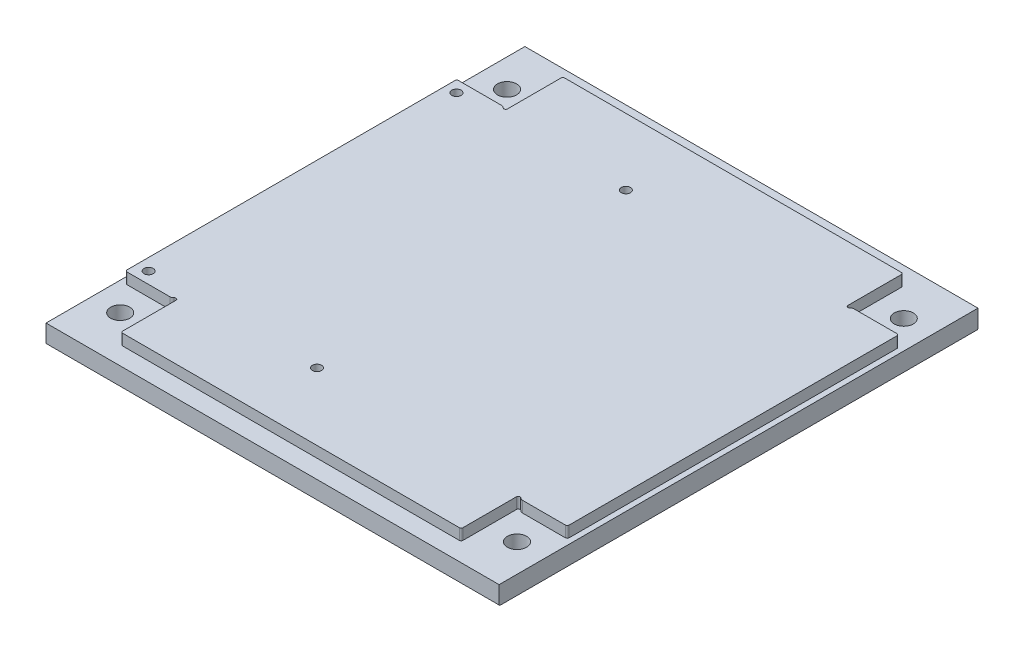
SolidWorks part; units mm, degrees
ref_plane "Front Plane" through (0, 0, 0) normal (0, 0, 1) x (1, 0, 0)
ref_plane "Top Plane" through (0, 0, 0) normal (0, 1, 0) x (1, 0, 0)
ref_plane "Right Plane" through (0, 0, 0) normal (1, 0, 0) x (0, 0, -1)
other "Configuration Table"
sketch "草图1" plane through (0, 0, 0) normal (0, 1, 0) x (1, 0, 0)
  line L0 (-61.5, 65) -> (-61.5, -65)
  line L1 (-61.5, -65) -> (61.5, -65)
  line L2 (61.5, -65) -> (61.5, 65)
  line L3 (61.5, 65) -> (-61.5, 65)
extrude "凸台-拉伸1" add sketch "草图1" against normal blind 5
sketch "草图2" plane through (0, 0, 0) normal (0, 1, 0) x (-1, 0, 0)
  line L0 (46.2, -45) -> (46.2, -60)
  line L1 (46.2, -60) -> (-46.2, -60)
  line L2 (-46.2, -60) -> (-46.2, -45)
  line L3 (-47.2, -45) -> (-60, -45)
  line L4 (-60, -45) -> (-60, 45)
  line L5 (-60, 45) -> (-47.2, 45)
  line L6 (-46.2, 45) -> (-46.2, 60)
  line L7 (-46.2, 60) -> (46.2, 60)
  line L8 (46.2, 60) -> (46.2, 45)
  line L9 (47.2, 45) -> (60, 45)
  line L10 (60, 45) -> (60, -45)
  line L11 (60, -45) -> (47.2, -45)
  arc A0 (47.2, -45) -> (46.2, -45) centre (46.7, -45) ccw
  arc A1 (-46.2, -45) -> (-47.2, -45) centre (-46.7, -45) ccw
  arc A2 (-47.2, 45) -> (-46.2, 45) centre (-46.7, 45) ccw
  arc A3 (46.2, 45) -> (47.2, 45) centre (46.7, 45) ccw
extrude "凸台-拉伸2" add sketch "草图2" along normal blind 3
hole_wizard "Ø13.0 (13) 直径孔1" positions "草图4" profile "草图3" hole size "Ø13.0" standard "ANSI Metric"
sketch "草图4" plane through (0, -5, 0) normal (0, -1, 0) x (-1, 0, 0)
  point P0 (0, 0)
sketch "草图3" plane through (0, -5, 0) normal (1, 0, 0) x (0, 0, -1)
  line L0 (0, 0) -> (0, 6)
  line L1 (0, 6) -> (6.5, 6)
  line L2 (6.5, 6) -> (6.5, 0)
  line L5 (6.5, 0) -> (0, 0)
  line L10 (0, 6) -> (-6.5, 6) construction
  line L11 (0, -6.35) -> (0, 107.95) construction
  dimension "孔直径" = 13
  dimension "孔深度" = 6
  dimension "导头角度" = 180
hole_wizard "Ø2.5 (2.5) 直径孔1" positions "草图6" profile "草图5" hole size "Ø2.5" standard "ANSI Metric"
sketch "草图6" plane through (0, 3, 0) normal (0, 1, 0) x (1, 0, 0)
  point P0 (-56.7806, -41.8553)
  point P1 (-11.0414, 41.9563)
  point P2 (-56.9076, 41.8378)
  point P3 (-11.1684, -41.7598)
sketch "草图5" plane through (-56.7806, 3, 41.8553) normal (1, 0, 0) x (0, 0, 1)
  line L0 (0, 0) -> (0, 5)
  line L1 (0, 5) -> (1.25, 5)
  line L2 (1.25, 5) -> (1.25, 0)
  line L5 (1.25, 0) -> (0, 0)
  line L10 (0, 5) -> (-1.25, 5) construction
  line L11 (0, -6.35) -> (0, 107.95) construction
  dimension "孔直径" = 2.5
  dimension "孔深度" = 5
  dimension "导头角度" = 180
hole_wizard "Ø3.3 (3.3) 直径孔1" positions "草图8" profile "草图7" hole size "Ø3.3" standard "ANSI Metric"
sketch "草图8" plane through (0, -5, 0) normal (0, -1, 0) x (-1, 0, 0)
  point P0 (-14.7224, -8.5)
  point P1 (-14.7224, 8.5)
  point P2 (0, 17)
  point P3 (14.7224, 8.5)
  point P4 (14.7224, -8.5)
  point P5 (0, -17)
sketch "草图7" plane through (14.7224, -5, 8.5) normal (1, 0, 0) x (0, 0, -1)
  line L0 (0, 0) -> (0, 6)
  line L1 (0, 6) -> (1.65, 6)
  line L2 (1.65, 6) -> (1.65, 0)
  line L5 (1.65, 0) -> (0, 0)
  line L10 (0, 6) -> (-1.65, 6) construction
  line L11 (0, -6.35) -> (0, 107.95) construction
  dimension "孔直径" = 3.3
  dimension "孔深度" = 6
  dimension "导头角度" = 180
hole_wizard "孔1" positions "草图10" profile "草图9" legacy
sketch "草图10" plane through (0, -5, 0) normal (0, -1, 0) x (-1, 0, 0)
  point P0 (53.85, 52.5)
  point P1 (-53.85, -52.5)
  point P2 (53.85, -52.5)
  point P3 (-53.85, 52.5)
sketch "草图9" plane through (-53.85, -5, -52.5) normal (1, 0, 0) x (0, 0, -1)
  line L0 (0, 0) -> (0, 8)
  line L1 (0, 8) -> (2.6, 8)
  line L2 (2.6, 8) -> (2.6, 1)
  line L3 (2.6, 1) -> (5.5, 1)
  line L4 (5.5, 1) -> (5.5, 0)
  line L5 (5.5, 0) -> (0, 0)
  line L6 (0, 110) -> (0, -10) construction
  dimension "直径" = 5.2
  dimension "深度" = 8
  dimension "柱坑直径" = 11
  dimension "柱坑深度" = 1
chamfer "倒角1" distance 0.2 angle 45 2 edges at (0, -5, 65) (0, -5, -65)
fillet "圆角1" radius 0.5 8 edges at (-60, 1.5, -45) (-46.2, 1.5, 60) (46.2, 1.5, 60) (-60, 1.5, 45) (-46.2, 1.5, -60) (60, 1.5, 45) (46.2, 1.5, -60) (60, 1.5, -45)
fillet "圆角2" radius 1 4 edges at (-47.2, 1.5, -45) (-47.2, 1.5, 45) (47.2, 1.5, -45) (47.2, 1.5, 45)
